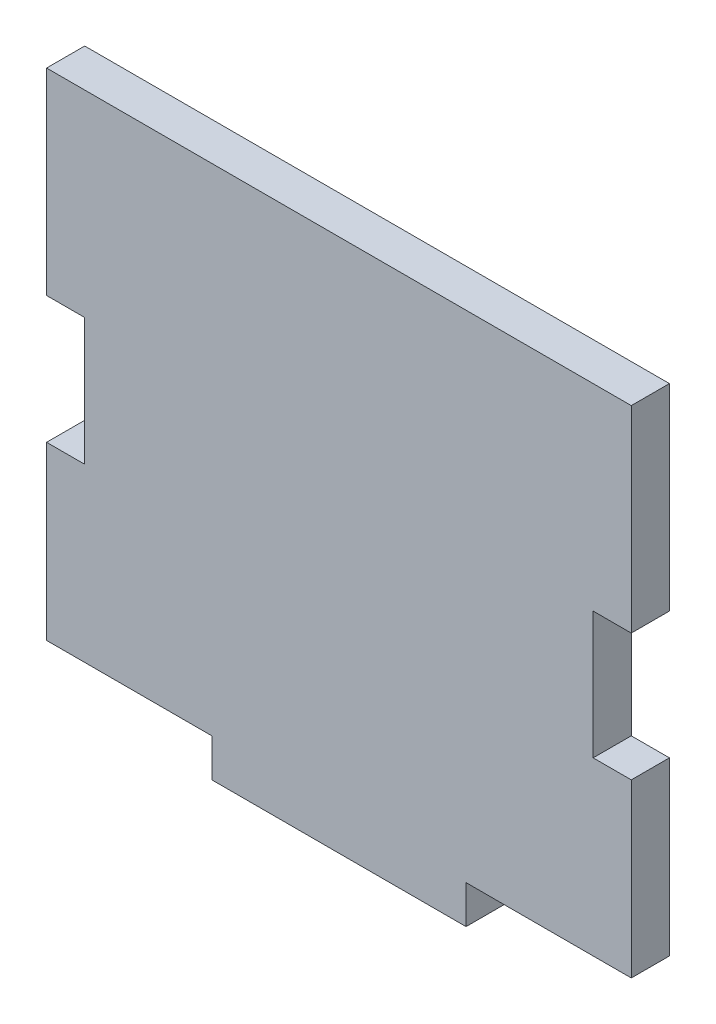
SolidWorks part; units mm, degrees
ref_plane "Front Plane" through (0, 0, 0) normal (0, 0, 1) x (1, 0, 0)
ref_plane "Top Plane" through (0, 0, 0) normal (0, 1, 0) x (1, 0, 0)
ref_plane "Right Plane" through (0, 0, 0) normal (1, 0, 0) x (0, 0, -1)
sketch "Sketch1" plane through (0, 0, 0) normal (0, 0, 1) x (1, 0, 0)
  line L0 (0, 0) -> (0, 21) construction
  line L1 (-23, 21) -> (23, 21)
  line L2 (-23, 21) -> (-23, -21)
  line L3 (-23, -21) -> (23, -21)
  line L4 (23, 21) -> (23, -21)
  line L5 (0, 0) -> (23, 0) construction
  dimension "D1" = 46
  dimension "D2" = 42
extrude "Boss-Extrude1" add sketch "Sketch1" along normal blind 3
sketch "Sketch2" plane through (0, 0, 3) normal (0, 0, 1) x (1, 0, 0)
  line L0 (-23, 21) -> (-23, -21) construction
  line L1 (-23, -18) -> (-10, -18)
  line L2 (-23, -18) -> (-23, -21)
  line L3 (-23, -21) -> (-10, -21)
  line L4 (-10, -18) -> (-10, -21)
  line L5 (-23, -21) -> (23, -21) construction
  line L6 (0, 21) -> (0, -21) construction
  line L7 (10, -18) -> (23, -18)
  line L8 (10, -18) -> (10, -21)
  line L9 (10, -21) -> (23, -21)
  line L10 (23, -18) -> (23, -21)
  line L11 (23, 21) -> (-23, 21) construction
  dimension "D1" = 20
  dimension "D2" = 3
extrude "Cut-Extrude1" cut sketch "Sketch2" against normal through all
sketch "Sketch3" plane through (0, 0, 0) normal (0, 0, -1) x (-1, 0, 0)
  line L0 (-23, -18) -> (-23, 21) construction
  line L1 (-20, 5.5) -> (-23, 5.5)
  line L2 (-20, 5.5) -> (-20, -4.5)
  line L3 (-20, -4.5) -> (-23, -4.5)
  line L4 (-23, 5.5) -> (-23, -4.5)
  line L5 (-23, -4.5) -> (-20, -4.5) construction
  line L6 (23, 21) -> (23, -18) construction
  line L7 (20, 5.5) -> (23, 5.5)
  line L8 (20, 5.5) -> (20, -4.5)
  line L9 (20, -4.5) -> (23, -4.5)
  line L10 (23, 5.5) -> (23, -4.5)
  line L11 (20, -4.5) -> (23, -4.5) construction
extrude "Cut-Extrude2" cut sketch "Sketch3" against normal through all
